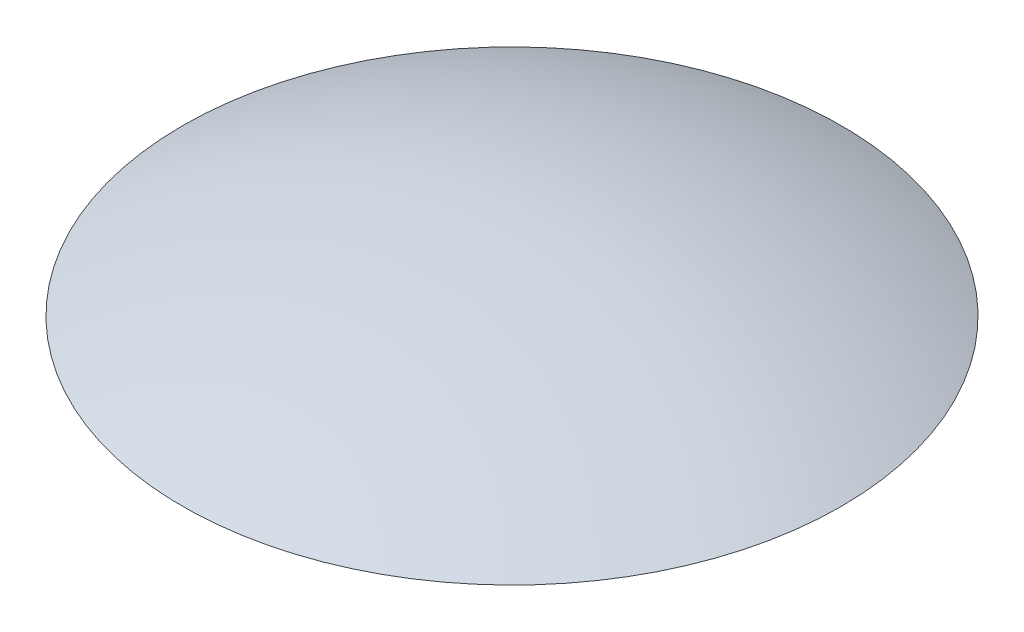
SolidWorks part; units mm, degrees
ref_plane "Plan de face" through (0, 0, 0) normal (0, 0, 1) x (1, 0, 0)
ref_plane "Plan de dessus" through (0, 0, 0) normal (0, 1, 0) x (1, 0, 0)
ref_plane "Plan de droite" through (0, 0, 0) normal (1, 0, 0) x (0, 0, -1)
sketch "Esquisse1" plane through (0, 0, 0) normal (0, 0, 1) x (1, 0, 0)
  line L0 (0, 15) -> (0, 0)
  line L1 (0, 0) -> (65.3835, 0)
  arc A0 (0, 15) -> (65.3835, 0) centre (0, -135) cw
  dimension "D2" = 150
  dimension "D1" = 15
revolve "Révolution1" add sketch "Esquisse1" angle 360 about L0
sketch "Esquisse4" plane through (0, 0, 0) normal (0, -1, 0) x (1, 0, 0)
  circle A0 centre (0, 0) radius 10.25
  dimension "D1" = 20.5
extrude "Enlèv. mat.-Extru.2" cut sketch "Esquisse4" against normal blind 11.65
sketch "Esquisse5" plane through (0, 0, 0) normal (0, -1, 0) x (1, 0, 0)
  circle A0 centre (0, 0) radius 35 construction
  circle A1 centre (35, 0) radius 10
  dimension "D1" = 70
  dimension "D2" = 20
extrude "Enlèv. mat.-Extru.3" cut sketch "Esquisse5" against normal blind 6
pattern_circular "Répétition circulaire1" count 3 every 120 about axis through (0, 0, 0) along (0, 1, 0) of "Enlèv. mat.-Extru.3"
